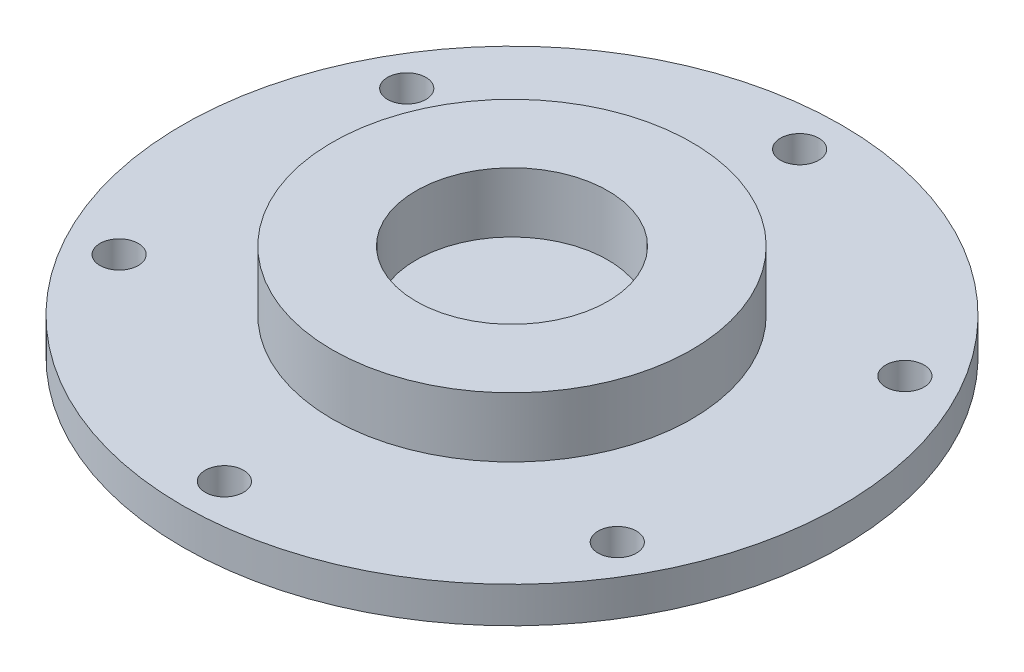
SolidWorks part; units mm, degrees
material "氧化铝"
ref_plane "前视基准面" through (0, 0, 0) normal (0, 0, 1) x (1, 0, 0)
ref_plane "上视基准面" through (0, 0, 0) normal (0, 1, 0) x (1, 0, 0)
ref_plane "右视基准面" through (0, 0, 0) normal (1, 0, 0) x (0, 0, -1)
sketch "草图1" plane through (0, 0, 0) normal (0, 1, 0) x (1, 0, 0)
  circle A0 centre (0, 0) radius 27.5
  dimension "D1" = 55
extrude "凸台-拉伸1" add sketch "草图1" along normal blind 3
sketch "草图2" plane through (0, 3, 0) normal (0, 1, 0) x (1, 0, 0)
  circle A0 centre (0, 0) radius 15
  dimension "D1" = 30
extrude "凸台-拉伸2" add sketch "草图2" along normal blind 5
sketch "草图4" plane through (0, 3, 0) normal (0, 1, 0) x (1, 0, 0)
  circle A0 centre (0, 24) radius 1.6
  dimension "D2" = 3.2
  dimension "D1" = 24
extrude "切除-拉伸1" cut sketch "草图4" against normal up to next
pattern_circular "阵列(圆周)1" count 6 over 360 about axis through (0, 0, 0) along (0, 1, 0) of "切除-拉伸1"
sketch "草图5" plane through (0, 8, 0) normal (0, 1, 0) x (1, 0, 0)
  circle A0 centre (0, 0) radius 8
  dimension "D1" = 16
extrude "切除-拉伸2" cut sketch "草图5" against normal blind 5
